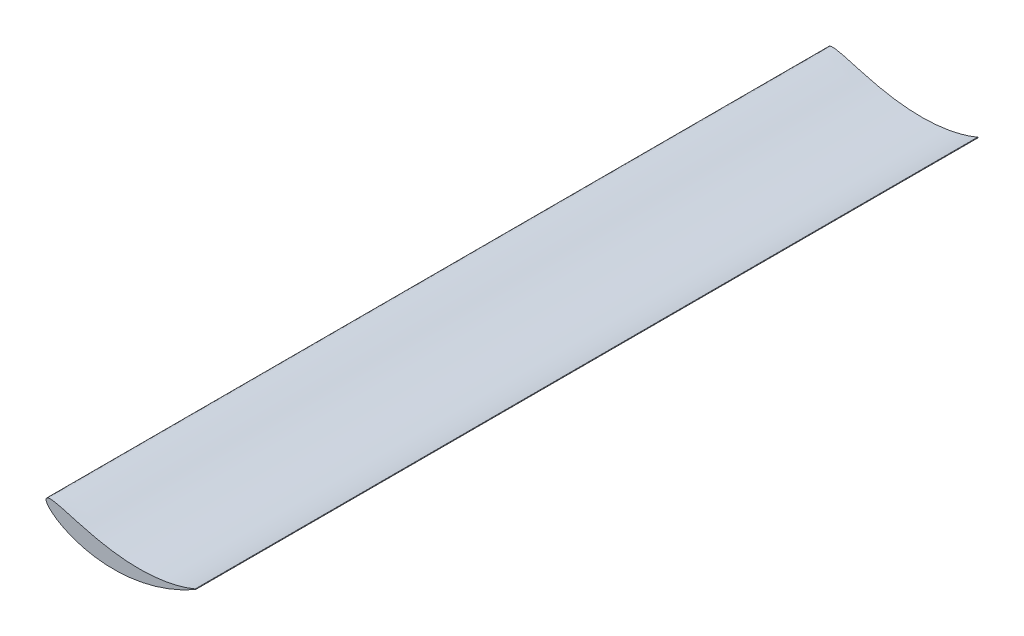
SolidWorks part; units mm, degrees
material "Thornel Mat VMA"
ref_plane "Front Plane" through (0, 0, 0) normal (0, 0, 1) x (1, 0, 0)
ref_plane "Top Plane" through (0, 0, 0) normal (0, 1, 0) x (1, 0, 0)
ref_plane "Right Plane" through (0, 0, 0) normal (1, 0, 0) x (0, 0, -1)
sketch "Sketch2" plane through (0, 0, 0) normal (0, 0, 1) x (1, 0, 0)
  line L0 (190.62, -4.1136) -> (190.9562, -4.7774) construction
  arc A1 (190.62, -4.1136) -> (190.9562, -4.7774) centre (190.7881, -4.4455) cw
  spline S2 degree 3 poles (190.9562, -4.7774) (190.8244, -4.8507) (189.2662, -5.7163) (186.0109, -7.4936) (180.8236, -10.2147) (174.6982, -13.256) (167.5914, -16.5396) (159.4883, -19.9547) (150.394, -23.3651) (140.3485, -26.6129) (129.4336, -29.5249) (117.7796, -31.924) (105.5695, -33.6483) (93.034, -34.5636) (80.4426, -34.5851) (68.0857, -33.687) (56.2533, -31.9099) (45.2123, -29.3578) (35.1866, -26.1865) (26.3435, -22.5854) (18.7877, -18.7593) (12.5633, -14.9069) (7.6602, -11.2053) (4.0276, -7.8032) (1.5737, -4.7963) (0.2015, -2.2527) (-0.2135, -0.069) (0.5971, 1.675) (2.3572, 2.5817) (4.673, 2.9191) (7.6021, 2.8309) (11.0992, 2.3531) (15.1231, 1.539) (19.6227, 0.4401) (24.5519, -0.887) (29.8679, -2.3863) (35.5308, -4.004) (41.5034, -5.6879) (47.7502, -7.3891) (54.2367, -9.0639) (60.9292, -10.6713) (67.7943, -12.1754) (74.7986, -13.5447) (81.9087, -14.7517) (89.091, -15.7747) (96.3114, -16.595) (103.5362, -17.1998) (110.731, -17.5802) (117.8618, -17.7316) (124.8949, -17.6543) (131.7964, -17.3523) (138.5333, -16.8343) (145.0728, -16.1129) (151.3832, -15.2049) (157.4332, -14.13) (163.1927, -12.9124) (168.6325, -11.5795) (173.7246, -10.1624) (178.4413, -8.6936) (182.7568, -7.2105) (186.6445, -5.7515) (189.2142, -4.7084) (190.4877, -4.1698) (190.62, -4.1136) knots 0.024528 0.024528 0.024528 0.024528 0.025589 0.037068 0.050855 0.066985 0.085458 0.106225 0.12918 0.154149 0.180883 0.209058 0.238272 0.268058 0.297904 0.32727 0.355624 0.382465 0.407356 0.429935 0.449939 0.467202 0.481655 0.493326 0.502345 0.508967 0.513684 0.517466 0.521651 0.527066 0.533952 0.5423 0.552018 0.562982 0.575063 0.588129 0.602057 0.616727 0.632029 0.647858 0.664118 0.680718 0.697573 0.714603 0.731732 0.74889 0.766005 0.783014 0.799852 0.816455 0.832763 0.848714 0.864247 0.879299 0.893808 0.90771 0.920938 0.933424 0.945097 0.955881 0.965701 0.974472 0.97549 0.97549 0.97549 0.97549
extrude "Boss-Extrude2" add sketch "Sketch2" along normal mid plane 1000 contours S2 A1
